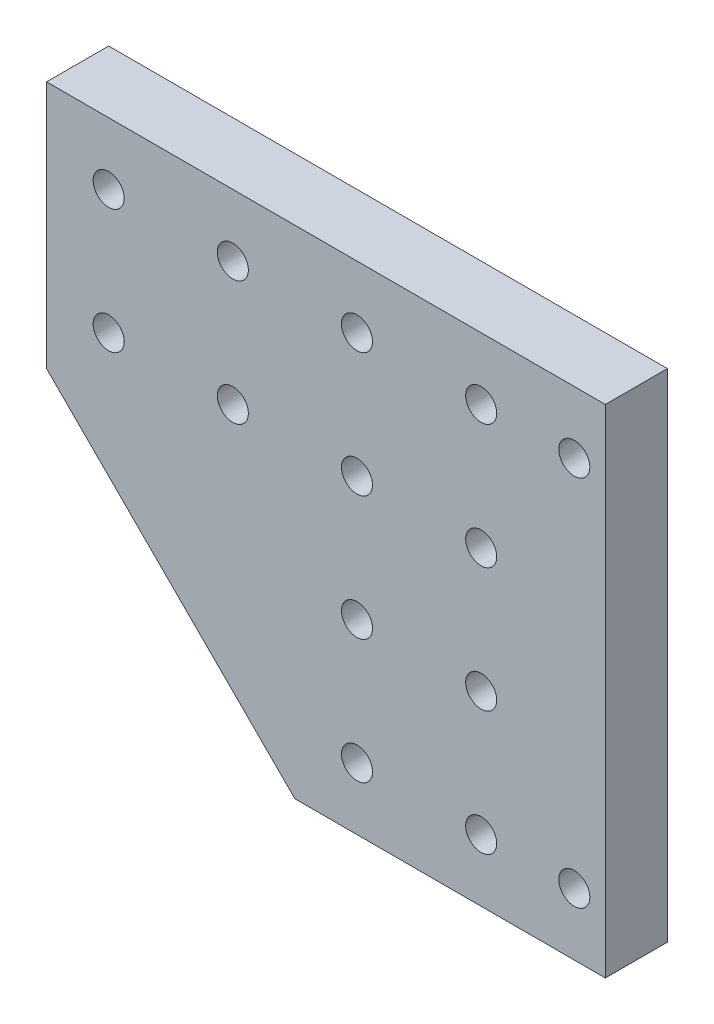
SolidWorks part; units mm, degrees
ref_plane "Front Plane" through (0, 0, 0) normal (0, 0, 1) x (1, 0, 0)
ref_plane "Top Plane" through (0, 0, 0) normal (0, 1, 0) x (1, 0, 0)
ref_plane "Right Plane" through (0, 0, 0) normal (1, 0, 0) x (0, 0, -1)
sketch "Sketch1" plane through (0, 0, 0) normal (0, 0, 1) x (1, 0, 0)
  line L0 (0, 0) -> (50, 0)
  line L1 (50, 0) -> (50, 80)
  line L2 (50, 80) -> (-40, 80)
  line L3 (-40, 80) -> (-40, 40)
  line L4 (-40, 40) -> (0, 0)
  dimension "D1" = 90
  dimension "D2" = 80
  dimension "D3" = 50
  dimension "D4" = 40
extrude "Boss-Extrude1" add sketch "Sketch1" along normal blind 10
sketch "Sketch2" plane through (0, 0, 10) normal (0, 0, 1) x (1, 0, 0)
  line L0 (0, 0) -> (50, 0) construction
  line L1 (50, 0) -> (50, 80) construction
  circle A0 centre (10, 10) radius 2.5
  circle A1 centre (30, 10) radius 2.5
  circle A2 centre (10, 30) radius 2.5
  circle A3 centre (30, 30) radius 2.5
  circle A4 centre (10, 50) radius 2.5
  circle A5 centre (30, 50) radius 2.5
  circle A6 centre (10, 70) radius 2.5
  circle A7 centre (30, 70) radius 2.5
  circle A8 centre (-30, 50) radius 2.5
  circle A9 centre (-10, 50) radius 2.5
  circle A10 centre (-30, 70) radius 2.5
  circle A11 centre (-10, 70) radius 2.5
  circle A12 centre (45, 10) radius 2.5
  circle A13 centre (45, 70) radius 2.5
  point P14 (0, 0)
  point P15 (0, 0)
  point P16 (0, 0)
  dimension "D1" = 10
  dimension "D9" = 5
  dimension "D10" = 5
  dimension "D2" = 20
  dimension "D3" = 20
  dimension "D4" = 20
  dimension "D5" = 20
  dimension "D6" = 20
  dimension "D7" = 20
  dimension "D8" = 20
extrude "Cut-Extrude1" cut sketch "Sketch2" against normal up to next
